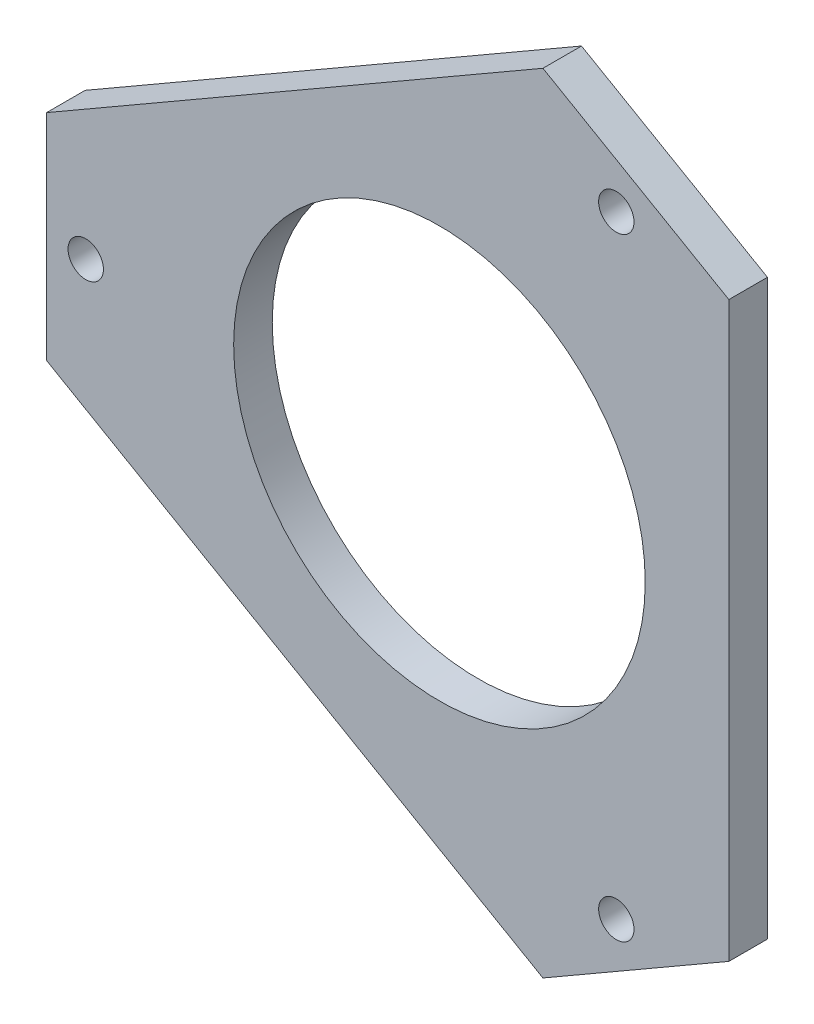
SolidWorks part; units mm, degrees
ref_plane "Plano frontal" through (0, 0, 0) normal (0, 0, 1) x (1, 0, 0)
ref_plane "Plano superior" through (0, 0, 0) normal (0, 1, 0) x (1, 0, 0)
ref_plane "Plano direito" through (0, 0, 0) normal (1, 0, 0) x (0, 0, -1)
sketch "Esboço1" plane through (0, 0, 10) normal (0, 0, 1) x (1, 0, 0)
  line L0 (16.091, 61.2517) -> (45, 44.5611)
  line L1 (45, 77.9423) -> (-90, 0) construction
  line L2 (-90, 0) -> (45, -77.9423) construction
  line L3 (45, -77.9423) -> (45, 77.9423) construction
  line L4 (45, 44.5611) -> (45, -44.5611)
  line L5 (45, -44.5611) -> (16.091, -61.2517)
  line L6 (16.091, -61.2517) -> (-61.091, -16.6906)
  line L7 (-61.091, -16.6906) -> (-61.091, 16.6906)
  line L8 (-61.091, 16.6906) -> (16.091, 61.2517)
  line L9 (118.1655, 0) -> (118.1655, -4.1075)
  circle A0 centre (0, 0) radius 90 construction
  circle A1 centre (0, 0) radius 63.33 construction
  circle A2 centre (0, 0) radius 32
  dimension "D1" = 180
  dimension "D2" = 64
extrude "Ressalto-extrusão1" add sketch "Esboço1" along normal blind 6 contours L8 L0 L4 L5 L6 L7 | A2
sketch "Esboço2" plane through (0, 0, 16) normal (0, 0, 1) x (1, 0, 0)
  line L1 (27.5, 47.6314) -> (-55, 0)
  line L2 (-55, 0) -> (27.5, -47.6314)
  line L3 (27.5, -47.6314) -> (27.5, 47.6314)
  circle A0 centre (0, 0) radius 55 construction
hole_wizard "Furo com folga de M51" positions "3DSketch1" profile "Esboço3" hole size "M5" standard "ISO" end condition up to next
sketch3d "3DSketch1"
  point P0 (-55, 0, 16)
  point P3 (27.5, 47.6314, 16)
  point P6 (27.5, -47.6314, 16)
sketch "Esboço3" plane through (-55, 0, 16) normal (1, 0, 0) x (0, -1, 0)
  line L0 (0, 0) -> (0, 6)
  line L1 (0, 6) -> (2.75, 6)
  line L2 (2.75, 6) -> (2.75, 0)
  line L5 (2.75, 0) -> (0, 0)
  line L11 (0, -6.35) -> (0, 107.95) construction
  dimension "Thru Hole Dia." = 5.5
  dimension "Thru Hole Depth" = 6
